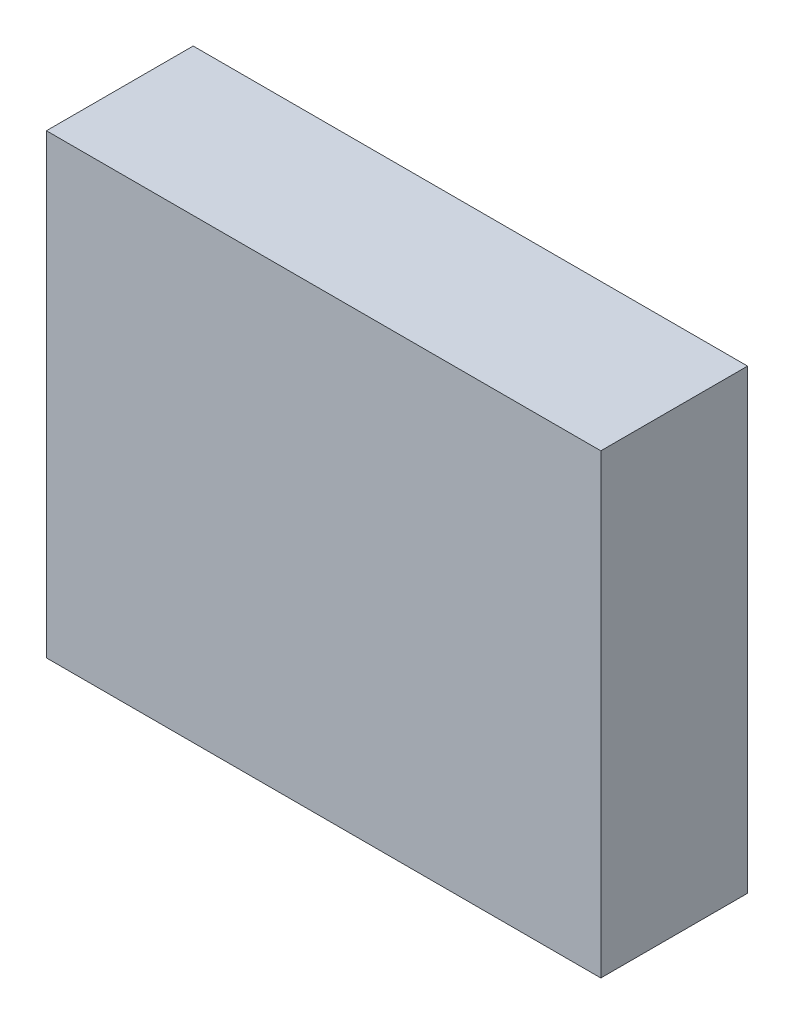
SolidWorks part; units mm, degrees
ref_plane "Front Plane" through (0, 0, 0) normal (0, 0, 1) x (1, 0, 0)
ref_plane "Top Plane" through (0, 0, 0) normal (0, 1, 0) x (1, 0, 0)
ref_plane "Right Plane" through (0, 0, 0) normal (1, 0, 0) x (0, 0, -1)
sketch "Sketch1" plane through (0, 0, 0) normal (0, 0, 1) x (1, 0, 0)
  line L1 (-107.95, -88.9) -> (107.95, -88.9)
  line L2 (-107.95, -88.9) -> (-107.95, 88.9)
  line L3 (-107.95, 88.9) -> (107.95, 88.9)
  line L4 (107.95, -88.9) -> (107.95, 88.9)
  line L5 (-107.95, -88.9) -> (107.95, 88.9) construction
  line L6 (-107.95, 88.9) -> (107.95, -88.9) construction
  point P0 (0, 0)
  dimension "D1" = 177.8
  dimension "D2" = 215.9
extrude "Boss-Extrude1" add sketch "Sketch1" along normal blind 57.15
